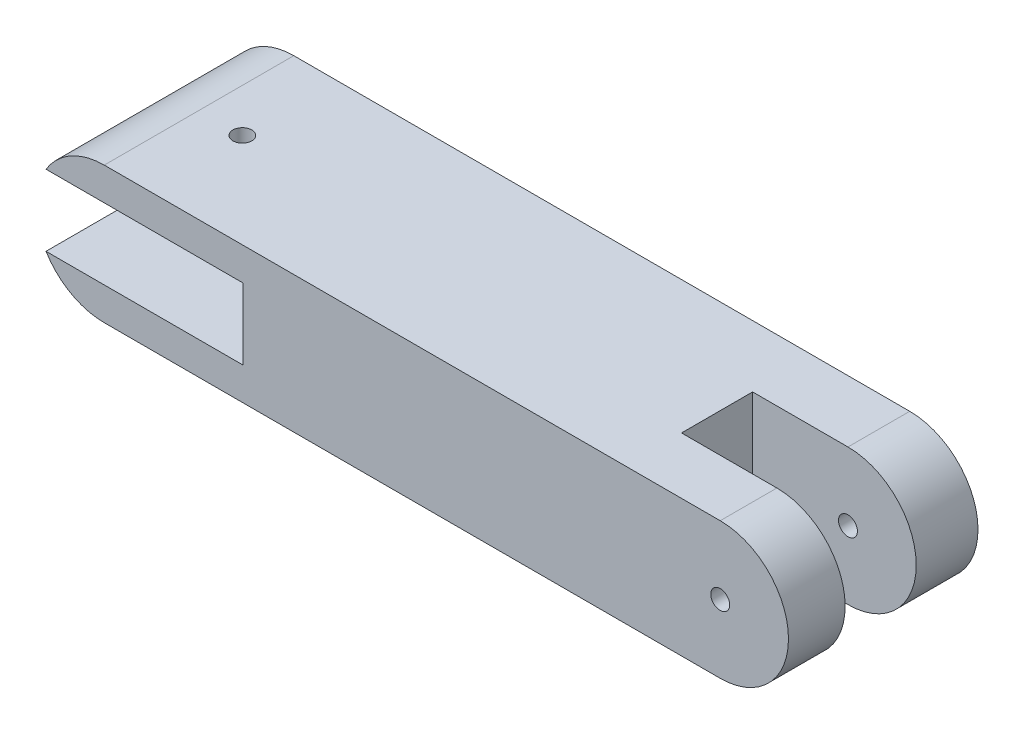
SolidWorks part; units mm, degrees
ref_plane "Plano frontal" through (0, 0, 0) normal (0, 0, 1) x (1, 0, 0)
ref_plane "Plano superior" through (0, 0, 0) normal (0, 1, 0) x (1, 0, 0)
ref_plane "Plano direito" through (0, 0, 0) normal (1, 0, 0) x (0, 0, -1)
sketch "Esboço1" plane through (0, 0, 0) normal (0, 0, 1) x (1, 0, 0)
  line L0 (-60.6729, 0) -> (-56.5569, 0) construction
  line L2 (-56.5569, 14.4058) -> (73.4431, 14.4058)
  line L4 (-56.5569, -14.4058) -> (73.4431, -14.4058)
  arc A0 (73.4431, 14.4058) -> (73.4431, -14.4058) centre (73.4431, 0) cw
  arc A1 (-56.5569, -14.4058) -> (-56.5569, 14.4058) centre (-56.5569, 0) cw
  point P0 (0, 0)
  point P4 (0, 0)
extrude "Ressalto-extrusão1" add sketch "Esboço1" along normal blind 40
sketch "Esboço2" plane through (0, 0, 40) normal (0, 0, 1) x (1, 0, 0)
  circle A0 centre (73.4431, 0) radius 2
extrude "Corte-extrusão1" cut sketch "Esboço2" against normal mid plane 80
sketch "Esboço3" plane through (0, 0, 40) normal (0, 0, 1) x (1, 0, 0)
  line L1 (-27.3239, 7.5) -> (-72.9173, 7.5)
  line L2 (-27.3239, 7.5) -> (-27.3239, -7.5)
  line L3 (-27.3239, -7.5) -> (-72.9173, -7.5)
  line L4 (-72.9173, 7.5) -> (-72.9173, -7.5)
  line L5 (-27.3239, 7.5) -> (-72.9173, -7.5) construction
  line L6 (-27.3239, -7.5) -> (-72.9173, 7.5) construction
  point P0 (-50.1206, 0)
extrude "Corte-extrusão2" cut sketch "Esboço3" against normal mid plane 80
sketch "Esboço4" plane through (0, 14.4058, 0) normal (0, 1, 0) x (1, 0, 0)
  circle A0 centre (-47.4134, -20) radius 2
extrude "Corte-extrusão3" cut sketch "Esboço4" against normal mid plane 80
sketch "Esboço6" plane through (0, 14.4058, 0) normal (0, 1, 0) x (1, 0, 0)
  line L1 (53.3182, -13.0405) -> (114.2314, -13.0405)
  line L2 (53.3182, -13.0405) -> (53.3182, -28.0405)
  line L3 (53.3182, -28.0405) -> (114.2314, -28.0405)
  line L4 (114.2314, -13.0405) -> (114.2314, -28.0405)
  point P0 (0, -20.5405)
extrude "Corte-extrusão5" cut sketch "Esboço6" against normal mid plane 125
